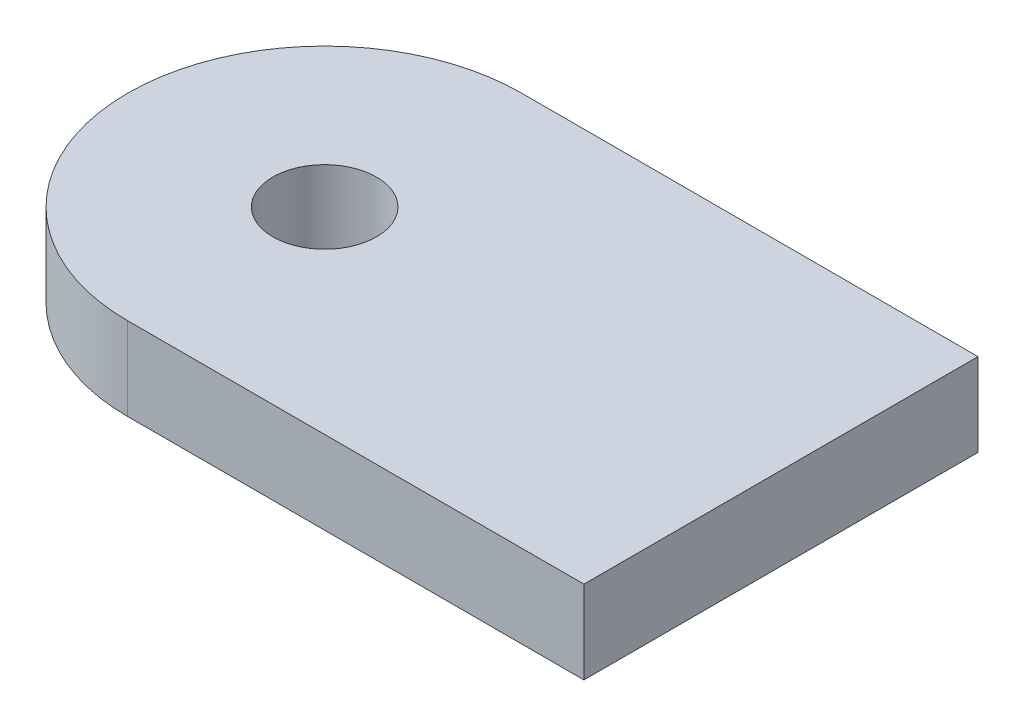
SolidWorks part; units mm, degrees
ref_plane "Front Plane" through (0, 0, 0) normal (0, 0, 1) x (1, 0, 0)
ref_plane "Top Plane" through (0, 0, 0) normal (0, 1, 0) x (1, 0, 0)
ref_plane "Right Plane" through (0, 0, 0) normal (1, 0, 0) x (0, 0, -1)
sketch "Sketch1" plane through (0, 0, 0) normal (0, 1, 0) x (1, 0, 0)
  line L0 (0, 0) -> (22, 0)
  line L1 (22, 0) -> (22, 19)
  line L2 (22, 19) -> (0, 19)
  line L4 (0, 19) -> (0, 0) construction
  arc A0 (0, 0) -> (0, 19) centre (0, 9.5) cw
  circle A1 centre (0, 9.5) radius 2.5
  dimension "D1" = 5
  dimension "D4" = 9.5
  dimension "D2" = 19
  dimension "D3" = 22
extrude "Boss-Extrude1" add sketch "Sketch1" along normal blind 4 contours L2 L4 A1 L0 L1 | L4 A0 A1
